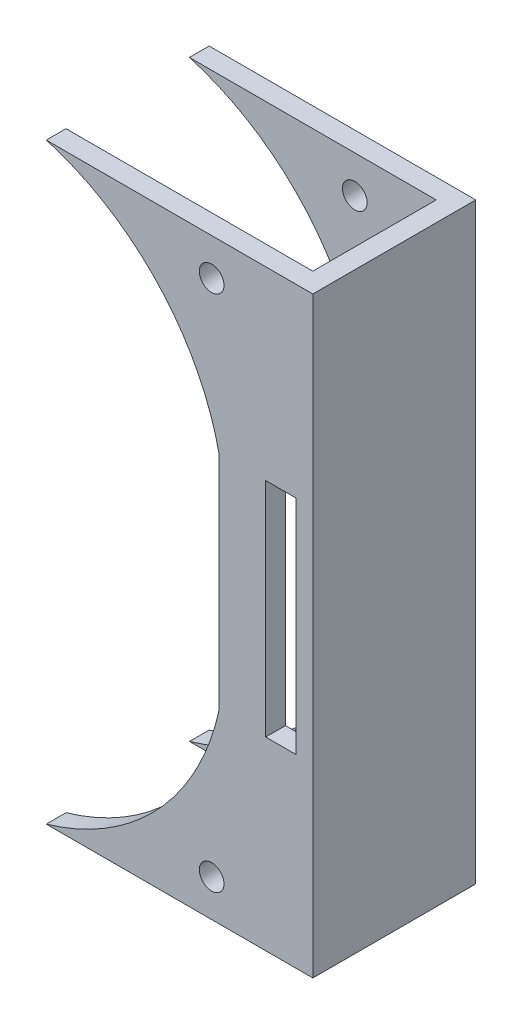
SolidWorks part; units mm, degrees
ref_plane "Front Plane" through (0, 0, 0) normal (0, 0, 1) x (1, 0, 0)
ref_plane "Top Plane" through (0, 0, 0) normal (0, 1, 0) x (1, 0, 0)
ref_plane "Right Plane" through (0, 0, 0) normal (1, 0, 0) x (0, 0, -1)
sketch "Sketch3" plane through (0, 0, 0) normal (0, 0, 1) x (1, 0, 0)
  line L0 (14.3358, 60) -> (14.3358, -60)
  line L1 (14.3358, -60) -> (-22.6642, -60)
  line L2 (12.3358, 22.5) -> (12.3358, -22.5)
  line L3 (14.3358, 60) -> (-22.6642, 60)
  line L4 (14.3358, 0) -> (10.3358, 0) construction
  line L5 (14.3358, 60) -> (27.3358, 60)
  line L6 (27.3358, 60) -> (27.3358, -60)
  line L7 (27.3358, -60) -> (14.3358, -60)
  line L8 (0, 0) -> (24.6715, 0) construction
  arc A2 (12.3358, 22.5) -> (-22.6642, 60) centre (-36.6774, 11.8377) ccw
  arc A3 (-22.6642, -60) -> (12.3358, -22.5) centre (-36.6774, -11.8377) ccw
  point P8 (12.3358, 0)
  point P10 (-0.008, 46.0625)
  point P12 (-0.008, -46.0625)
  dimension "D5" = 2
  dimension "D1" = 120
  dimension "D2" = 37
  dimension "D3" = 37
  dimension "D4" = 45
  dimension "D6" = 20
  dimension "D7" = 20
  dimension "D8" = 13
extrude "Boss-Extrude1" add sketch "Sketch3" along normal blind 4 contours L7 L6 L5 L0 | L4 L0 L3 A2 L2 | L0 L4 L2 A3 L1
ref_plane "Plane3" through (0, 0, -12.5) normal (0, 0, 1) x (1, 0, 0)
mirror "Mirror4" about plane through (0, 0, -12.5) normal (0, 0, 1) of bodies 101
sketch "Sketch11" plane through (27.3358, 0, 0) normal (1, 0, 0) x (0, 0, -1)
  line L1 (-4, 60) -> (29, 60)
  line L2 (-4, 60) -> (-4, -60)
  line L3 (-4, -60) -> (29, -60)
  line L4 (29, 60) -> (29, -60)
extrude "Boss-Extrude4" add sketch "Sketch11" along normal blind 4
sketch "Sketch12" plane through (0, 0, 4) normal (0, 0, 1) x (1, 0, 0)
  line L0 (-22.6642, 60) -> (31.3358, 60) construction
  line L1 (31.3358, 60) -> (31.3358, -60) construction
  circle A0 centre (10.8358, 52.5) radius 2.5
  dimension "D1" = 5
  dimension "D2" = 7.5
  dimension "D3" = 20.5
extrude "Cut-Extrude3" cut sketch "Sketch12" against normal through all
mirror "Mirror5" about plane through (0, 0, 0) normal (0, 1, 0) of "Cut-Extrude3"
sketch "Sketch13" plane through (0, 0, 4) normal (0, 0, 1) x (1, 0, 0)
  line L0 (31.3358, 60) -> (31.3358, -60) construction
  line L1 (21.7844, -22.5) -> (27.8872, -22.5)
  line L2 (21.7844, -22.5) -> (21.7844, 22.5)
  line L3 (21.7844, 22.5) -> (27.8872, 22.5)
  line L4 (27.8872, -22.5) -> (27.8872, 22.5)
  line L5 (21.7844, -22.5) -> (27.8872, 22.5) construction
  line L6 (21.7844, 22.5) -> (27.8872, -22.5) construction
  line L7 (12.3358, 0) -> (29.0962, 0) construction
  line L8 (12.3358, 22.5) -> (12.3358, -22.5) construction
  point P0 (24.8358, 0)
  dimension "D1" = 6.5
  dimension "D2" = 45
extrude "Cut-Extrude4" cut sketch "Sketch13" against normal through all
